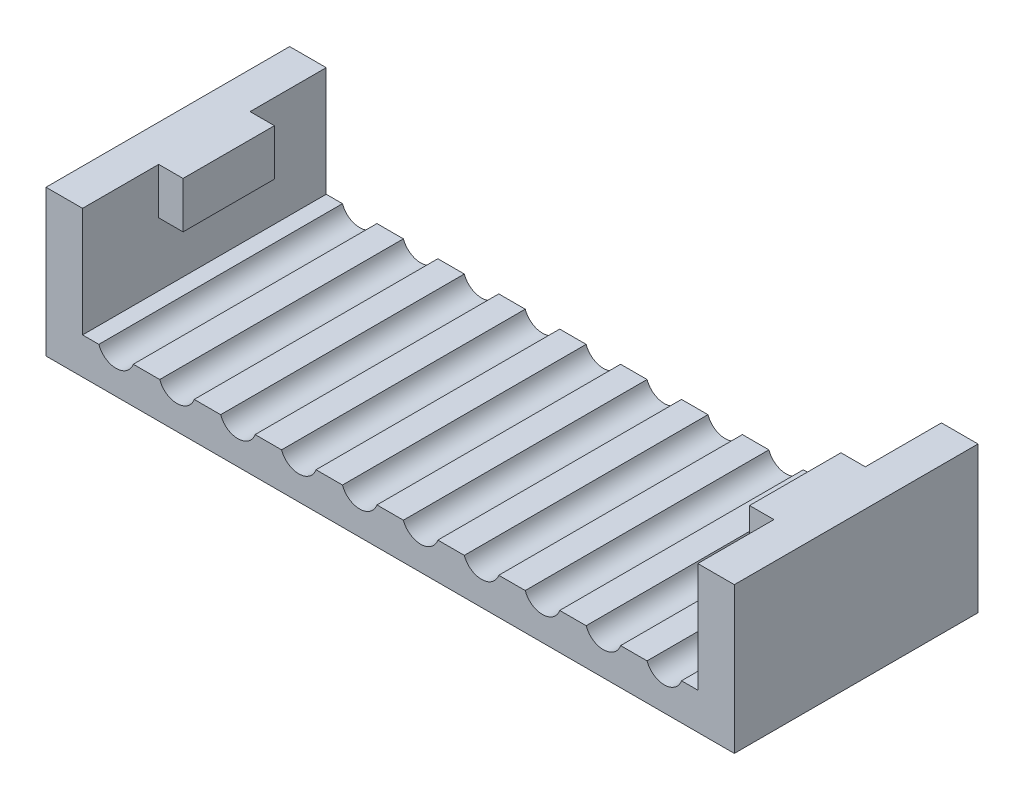
SolidWorks part; units mm, degrees
ref_plane "Front Plane" through (0, 0, 0) normal (0, 0, 1) x (1, 0, 0)
ref_plane "Top Plane" through (0, 0, 0) normal (0, 1, 0) x (1, 0, 0)
ref_plane "Right Plane" through (0, 0, 0) normal (1, 0, 0) x (0, 0, -1)
sketch "Sketch2" plane through (0, 0, 0) normal (0, 0, 1) x (1, 0, 0)
  line L0 (-12.625, 6) -> (-14.125, 6)
  line L1 (-14.125, 6) -> (-14.125, 0)
  line L2 (-14.125, 0) -> (14.125, 0)
  line L3 (14.125, 0) -> (14.125, 6)
  line L4 (14.125, 6) -> (12.625, 6)
  line L6 (12.625, 1.5) -> (-12.625, 1.5)
  line L10 (-12.625, 6) -> (-12.625, 1.5)
  line L13 (12.625, 6) -> (12.625, 1.5)
  point P6 (0, 0)
  point P7 (0, 0)
  point P9 (0, 0)
  point P10 (0, 0)
  point P12 (0, 0)
  dimension "D1" = 4.5
  dimension "D2" = 25.25
  dimension "D3" = 1.5
  dimension "D6" = 1.5
extrude "Boss-Extrude1" add sketch "Sketch2" along normal blind 10
sketch "Sketch3" plane through (0, 0, 10) normal (0, 0, 1) x (1, 0, 0)
  line L0 (-11.25, 1.75) -> (11.25, 1.75) construction
  line L1 (12.625, 1.5) -> (-12.625, 1.5) construction
  circle A0 centre (-11.25, 1.75) radius 0.75
  circle A1 centre (-8.75, 1.75) radius 0.75
  circle A2 centre (-6.25, 1.75) radius 0.75
  circle A3 centre (-3.75, 1.75) radius 0.75
  circle A4 centre (-1.25, 1.75) radius 0.75
  circle A5 centre (1.25, 1.75) radius 0.75
  circle A6 centre (3.75, 1.75) radius 0.75
  circle A7 centre (6.25, 1.75) radius 0.75
  circle A8 centre (8.75, 1.75) radius 0.75
  circle A9 centre (11.25, 1.75) radius 0.75
  point P3 (0, 0)
  point P5 (0, 0)
  point P6 (0, 1.5)
  point P24 (0, 1.75)
  point P26 (-1.45, 2.5)
  dimension "D1" = 2.5
  dimension "D4" = 1.5
  dimension "D2" = 10
  dimension "D3" = 0.25
extrude "Cut-Extrude1" cut sketch "Sketch3" against normal through all
sketch "Sketch4" plane through (-12.625, 0, 0) normal (1, 0, 0) x (0, 0, -1)
  line L0 (-10, 6) -> (0, 6) construction
  line L1 (-6.875, 6) -> (-3.125, 6)
  line L2 (-6.875, 6) -> (-6.875, 4.1)
  line L3 (-6.875, 4.1) -> (-3.125, 4.1)
  line L4 (-3.125, 6) -> (-3.125, 4.1)
  line L5 (-6.875, 6) -> (-3.125, 4.1) construction
  line L6 (-6.875, 4.1) -> (-3.125, 6) construction
  point P0 (-5, 5.05)
  point P7 (0, 0)
  point P8 (-4.4823, 8)
  point P9 (-5, 6)
  dimension "D1" = 1.9
  dimension "D2" = 3.75
extrude "Boss-Extrude2" add sketch "Sketch4" along normal blind 1
ref_plane "Plane1" through (0, 0, 0) normal (-1, 0, 0) x (0, 0, 1)
mirror "Mirror1" about plane through (0, 0, 0) normal (-1, 0, 0) of "Boss-Extrude2"
